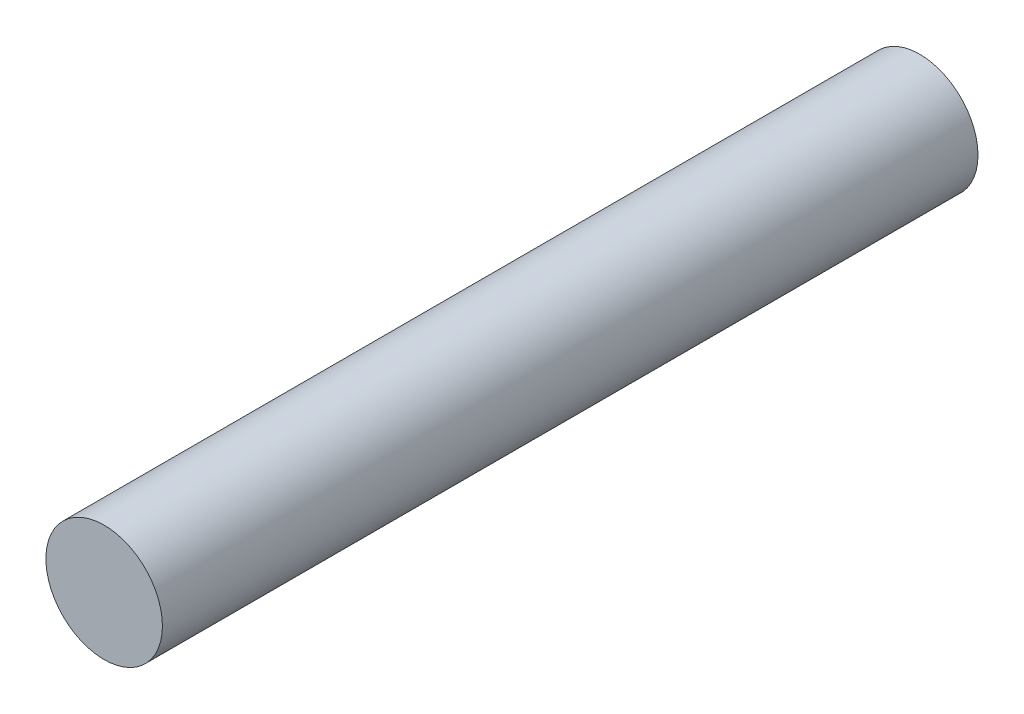
SolidWorks part; units mm, degrees
ref_plane "Front Plane" through (0, 0, 0) normal (0, 0, 1) x (1, 0, 0)
ref_plane "Top Plane" through (0, 0, 0) normal (0, 1, 0) x (1, 0, 0)
ref_plane "Right Plane" through (0, 0, 0) normal (1, 0, 0) x (0, 0, -1)
sketch "Sketch1" plane through (0, 0, 0) normal (0, 0, 1) x (1, 0, 0)
  circle A0 centre (0, 0) radius 63.5
  dimension "D1" = 127
extrude "Boss-Extrude1" add sketch "Sketch1" along normal blind 889
